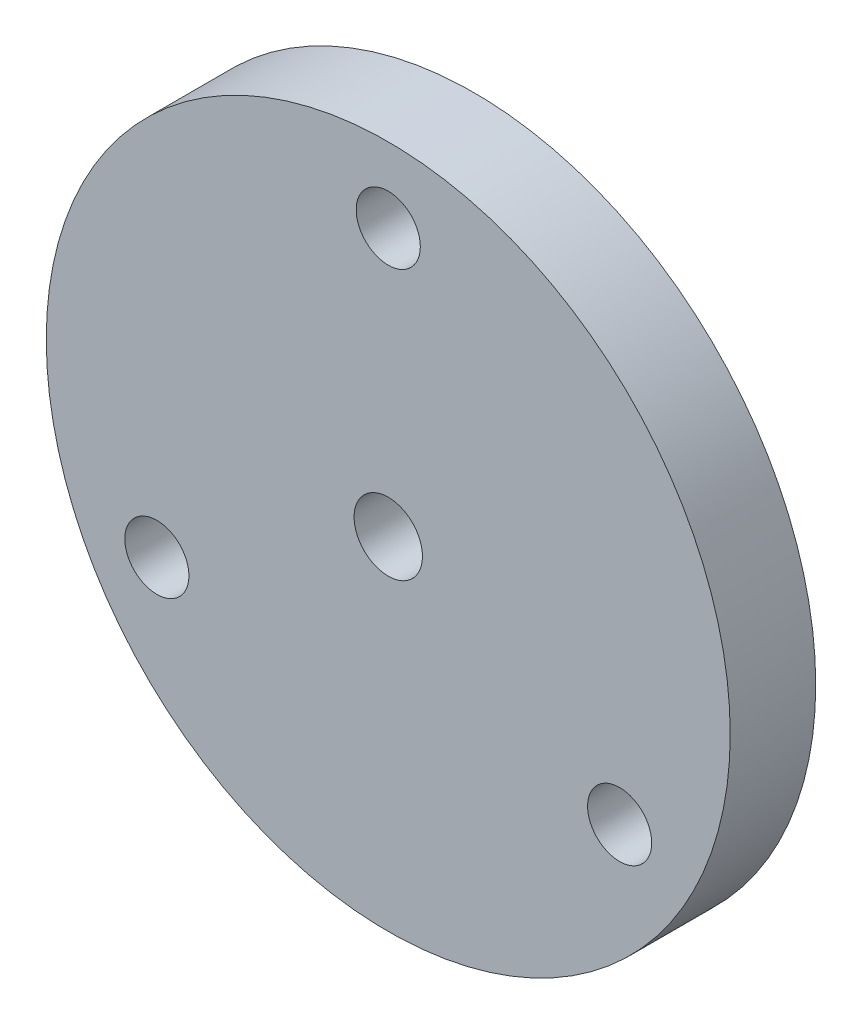
SolidWorks part; units mm, degrees
ref_plane "Alzado" through (0, 0, 0) normal (0, 0, 1) x (1, 0, 0)
ref_plane "Planta" through (0, 0, 0) normal (0, 1, 0) x (1, 0, 0)
ref_plane "Vista lateral" through (0, 0, 0) normal (1, 0, 0) x (0, 0, -1)
sketch "Croquis1" plane through (0, 0, 0) normal (0, 0, 1) x (1, 0, 0)
  line L0 (0, 15.1568) -> (0, -16.8288) construction
  line L1 (0, 0) -> (0, 12.5) construction
  circle A0 centre (0, 0) radius 16
  circle A1 centre (0, 0) radius 12.5 construction
  circle A2 centre (0, 12.5) radius 1.5
  circle A3 centre (10.8253, -6.25) radius 1.5
  circle A4 centre (-10.8253, -6.25) radius 1.5
  circle A5 centre (0, 0) radius 1.6
  dimension "D1" = 32
  dimension "D2" = 25
  dimension "D3" = 3
  dimension "D6" = 3.2
  dimension "D5" = 12.5
  dimension "D4" = 3
extrude "Saliente-Extruir1" add sketch "Croquis1" along normal blind 4
